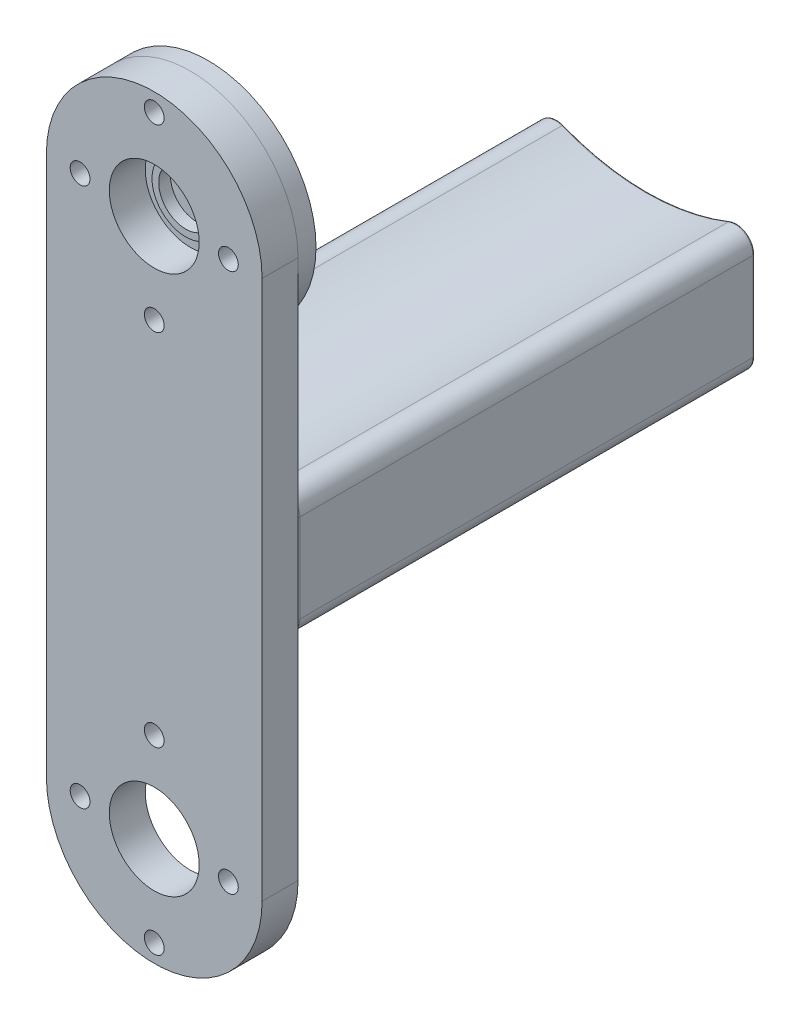
SolidWorks part; units mm, degrees
material "Полибутадиен (PB)"
ref_plane "Спереди" through (0, 0, 0) normal (0, 0, 1) x (1, 0, 0)
ref_plane "Сверху" through (0, 0, 0) normal (0, 1, 0) x (1, 0, 0)
ref_plane "Справа" through (0, 0, 0) normal (1, 0, 0) x (0, 0, -1)
sketch "Эскиз1" plane through (0, 0, 0) normal (1, 0, 0) x (0, 0, -1)
  line L0 (0, 3.75) -> (0, 12)
  line L1 (0, 12) -> (2, 12)
  line L2 (2, 12) -> (2, 4.5)
  line L3 (2, 4.5) -> (4.5, 4.5)
  line L4 (4.5, 4.5) -> (4.5, 3)
  line L5 (4.5, 3) -> (1.5, 3)
  line L6 (-0.5, 3.75) -> (0, 3.75)
  line L7 (-0.5, 3.75) -> (-0.5, 3)
  line L8 (-0.5, 3) -> (0.8, 3)
  line L9 (0.8, 3) -> (0.8, 1.4)
  line L10 (0.8, 1.4) -> (1.5, 1.4)
  line L11 (1.5, 3) -> (1.5, 1.4)
  dimension "D1" = 2
  dimension "D2" = 3
  dimension "D3" = 12
  dimension "D4" = 4.5
  dimension "D5" = 3
  dimension "D6" = 3.75
  dimension "D7" = 3
  dimension "D8" = 0.5
  dimension "D9" = 4.5
  dimension "D10" = 1.3
  dimension "D11" = 1.4
ref_axis "Ось1" through (0, 0, 50) along (0, 0, -1)
revolve "Повернуть1" add sketch "Эскиз1" angle 360 about axis through (0, 0, 50) along (0, 0, -1)
sketch "Эскиз2" plane through (0, 0, 0) normal (0, 0, 1) x (1, 0, 0)
  line L0 (0, 0) -> (8.25, 0) construction
  line L1 (0, 0) -> (7.7525, -2.8217) construction
  line L2 (0, 0) -> (0, 7) construction
  line L3 (0, 0) -> (2.3941, 6.5778) construction
  line L4 (0, 0) -> (0, 7) construction
  line L5 (0, 0) -> (-2.3941, 6.5778) construction
  circle A0 centre (8.25, 0) radius 0.75
  circle A1 centre (7.7525, -2.8217) radius 0.75
  circle A2 centre (7.7525, 2.8217) radius 0.75
  circle A3 centre (-8.25, 0) radius 0.75
  circle A4 centre (-7.7525, -2.8217) radius 0.75
  circle A5 centre (-7.7525, 2.8217) radius 0.75
  circle A6 centre (0, 7) radius 0.75
  circle A8 centre (0, 10) radius 0.75
  circle A9 centre (2.3941, 6.5778) radius 0.75
  circle A10 centre (3.4202, 9.3969) radius 0.75
  circle A11 centre (-2.3941, 6.5778) radius 0.75
  circle A12 centre (-3.4202, 9.3969) radius 0.75
  circle A13 centre (0, -7) radius 0.75
  circle A14 centre (0, -10) radius 0.75
  circle A15 centre (3.4202, -9.3969) radius 0.75
  circle A16 centre (2.3941, -6.5778) radius 0.75
  circle A17 centre (-2.3941, -6.5778) radius 0.75
  circle A18 centre (-3.4202, -9.3969) radius 0.75
  point P12 (0, 0)
  point P20 (0, 0)
  point P51 (0, 0)
  dimension "D1" = 1.5
  dimension "D7" = 1.5
  dimension "D9" = 1.5
  dimension "D2" = 8.25
  dimension "D4" = 20
  dimension "D8" = 7
  dimension "D10" = 10
  dimension "D12" = 20
  dimension "D14" = 20
  dimension "D3" = 2
  dimension "D5" = 2
  dimension "D6" = 2
  dimension "D11" = 2
  dimension "D13" = 2
  dimension "D15" = 2
extrude "Вырез-Вытянуть1" cut sketch "Эскиз2" against normal through all
sketch "스케치1" plane through (0, 0, 0) normal (0, 0, 1) x (1, 0, 0)
  line L0 (-12, 0) -> (-12, -60)
  line L1 (-12, -30) -> (12, -30) construction
  line L2 (12, -60) -> (12, 0)
  circle A0 centre (0, 0) radius 5
  circle A1 centre (0, 0) radius 12
  arc A2 (12, 0) -> (-12, 0) centre (0, 0) ccw
  circle A3 centre (-8.25, 0) radius 0.75 construction
  circle A4 centre (0, -10) radius 0.75 construction
  circle A5 centre (8.25, 0) radius 0.75 construction
  circle A6 centre (0, 10) radius 0.75 construction
  circle A7 centre (-8.25, 0) radius 0.75 construction
  circle A8 centre (0, -10) radius 0.75 construction
  circle A9 centre (8.25, 0) radius 0.75 construction
  circle A10 centre (0, 10) radius 0.75 construction
  arc A15 (12, -60) -> (-12, -60) centre (0, -60) cw
  circle A16 centre (0, -60) radius 5
  circle A17 centre (-8.25, 0) radius 1.1
  circle A18 centre (0, 10) radius 1.1
  circle A19 centre (8.25, 0) radius 1.1
  circle A20 centre (0, -10) radius 1.1
  circle A21 centre (0, -50) radius 1.1
  circle A22 centre (0, -50) radius 0.75 construction
  circle A23 centre (8.25, -60) radius 1.1
  circle A24 centre (8.25, -60) radius 0.75 construction
  circle A25 centre (-8.25, -60) radius 1.1
  circle A26 centre (-8.25, -60) radius 0.75 construction
  circle A27 centre (0, -70) radius 1.1
  circle A28 centre (0, -70) radius 0.75 construction
  circle M7 centre (3.4202, -9.3969) radius 0.75
  circle M8 centre (2.3941, -6.5778) radius 0.75
  circle M9 centre (-3.4202, -9.3969) radius 0.75
  circle M10 centre (-2.3941, -6.5778) radius 0.75
  circle M12 centre (0, -7) radius 0.75
  circle M13 centre (-3.4202, 9.3969) radius 0.75
  circle M14 centre (-2.3941, 6.5778) radius 0.75
  circle M15 centre (3.4202, 9.3969) radius 0.75
  circle M16 centre (2.3941, 6.5778) radius 0.75
  circle M18 centre (-7.7525, -2.8217) radius 0.75
  circle M19 centre (-7.7525, 2.8217) radius 0.75
  circle M21 centre (7.7525, 2.8217) radius 0.75
  circle M22 centre (0, 7) radius 0.75
  circle M23 centre (7.7525, -2.8217) radius 0.75
  circle M25 centre (0, 0) radius 12
  dimension "D3" = 10
  dimension "D4" = 2.2
  dimension "D2" = 30
  dimension "D1" = 0
extrude "보스-돌출1" add sketch "스케치1" along normal blind 4 separate body contours A15 L2 L0 A25 A21 A16 A23 A27 M25 | A20 A19 A18 A17 A0 M25 M8 M10 M12 M14 M16 M18 M22 M23 M21 M19 M15 M13 M9 M7 | M13 | M14 | M22 | M16 | M15 | M21 | M23 | M18 | M19 | M10 | M9 | M12 | M8 | M7
sketch "스케치2" plane through (0, 0, 0) normal (0, 0, -1) x (-1, 0, 0)
  line L1 (-12, -30) -> (40.626, -30) construction
  line L2 (-12, -60) -> (-12, 0) construction
  line L3 (0, 0) -> (0, -60) construction
  line L5 (12, -60) -> (12, 0)
  line L6 (-12, 0) -> (-12, -60)
  line L7 (12, -34.9201) -> (12, -25.0799)
  line L8 (-12, -25.0799) -> (-12, -34.9201)
  arc A0 (9.2593, -36.7779) -> (-9.2593, -36.7779) centre (0, -60) ccw
  arc A1 (-9.2593, -23.2221) -> (9.2593, -23.2221) centre (0, 0) ccw
  arc A2 (9.2593, -36.7779) -> (12, -34.9201) centre (10, -34.9201) ccw
  arc A3 (-9.2593, -36.7779) -> (-12, -34.9201) centre (-10, -34.9201) cw
  arc A4 (-12, -60) -> (12, -60) centre (0, -60) ccw
  arc A5 (12, 0) -> (-12, 0) centre (0, 0) ccw
  arc A8 (9.2593, -23.2221) -> (12, -25.0799) centre (10, -25.0799) cw
  arc A9 (-9.2593, -23.2221) -> (-12, -25.0799) centre (-10, -25.0799) ccw
  circle A10 centre (-10, -25.0799) radius 0.95
  circle A11 centre (-10, -34.9201) radius 0.95
  circle A12 centre (10, -25.0799) radius 0.95
  circle A13 centre (10, -34.9201) radius 0.95
  circle A15 centre (-4, -30) radius 0.95
  circle A16 centre (4, -30) radius 0.95
  circle A17 centre (-10, -25.0799) radius 1.1
  circle A18 centre (-4, -30) radius 1.1
  circle A19 centre (4, -30) radius 1.1
  circle A20 centre (10, -25.0799) radius 1.1
  circle A21 centre (10, -34.9201) radius 1.1
  circle A22 centre (-10, -34.9201) radius 1.1
  line M18 (12, -60) -> (12, 0)
  line M20 (-12, 0) -> (-12, -60)
  dimension "D1" = 50
  dimension "D3" = 2
  dimension "D4" = 1.9
  dimension "D5" = 8
  dimension "D6" = 2.2
  dimension "D2" = 0
extrude "보스-돌출2" add sketch "스케치2" along normal blind 50.8 separate body contours A17 A10 | A18 A15 | A19 A16 | A20 A12 | A21 A13 | A22 A11 | A1 A9 A3 A0 A2 A8 A22 A21 A20 A19 A18 A17 M20 M18
fillet "필렛1" radius 0.2 28 edges at (9.05, -34.9201, -50.8) (9.05, -34.9201, 0) (-10.95, -34.9201, -50.8) (-10.95, -34.9201, 0) (-10.95, -25.0799, -50.8) (-10.95, -25.0799, 0) (-4.95, -30, -50.8) (-4.95, -30, 0) (3.05, -30, -50.8) (3.05, -30, 0) (11.1222, -23.4244, 0) (11.1222, -23.4244, -50.8) (12, -30, 0) (12, -30, -50.8) (11.1222, -36.5756, 0) (11.1222, -36.5756, -50.8) (0, -35, 0) (0, -35, -50.8) (-11.1222, -36.5756, 0) (-11.1222, -36.5756, -50.8) (-12, -30, 0) (-12, -30, -50.8) (-11.1222, -23.4244, 0) (-11.1222, -23.4244, -50.8) (0, -25, 0) (0, -25, -50.8) (9.05, -25.0799, -50.8) (9.05, -25.0799, 0)
